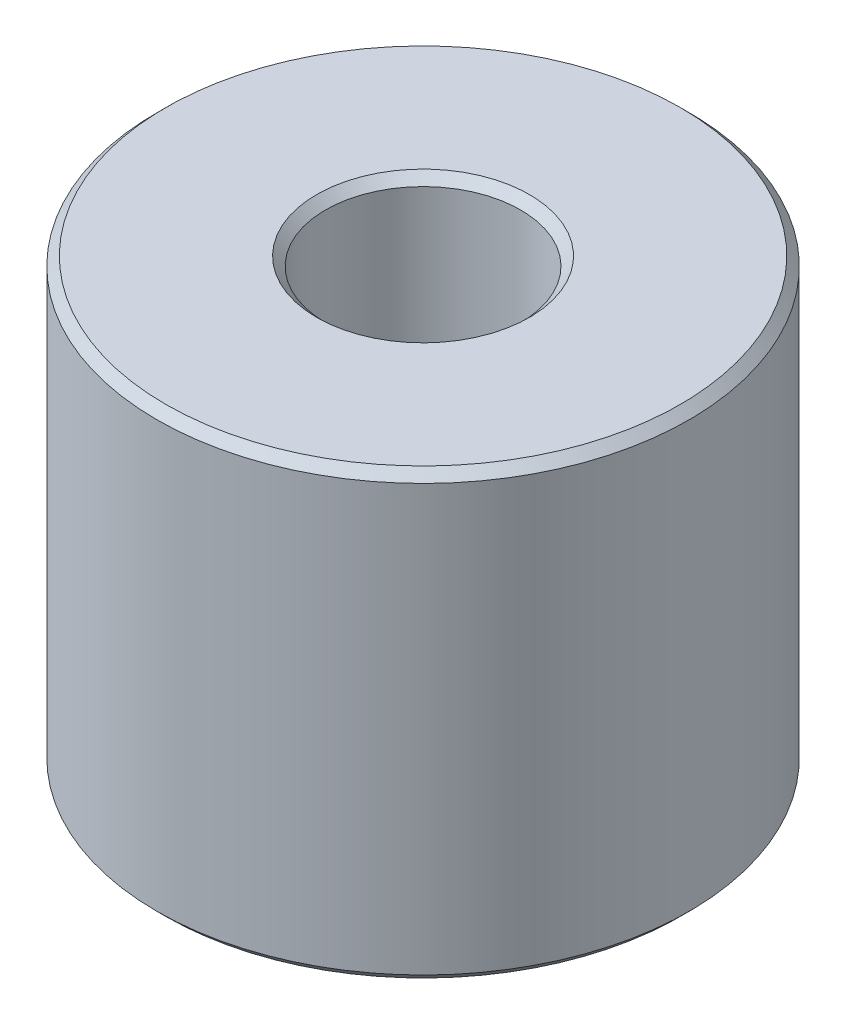
SolidWorks part; units mm, degrees
material "S45C"
ref_plane "正面" through (0, 0, 0) normal (0, 0, 1) x (1, 0, 0)
ref_plane "平面" through (0, 0, 0) normal (0, 1, 0) x (1, 0, 0)
ref_plane "右側面" through (0, 0, 0) normal (1, 0, 0) x (0, 0, -1)
sketch "ｽｹｯﾁ1" plane through (0, 0, 0) normal (0, 1, 0) x (1, 0, 0)
  circle A0 centre (0, 0) radius 1.1
  circle A1 centre (0, 0) radius 3
  dimension "D1" = 2.2
  dimension "D2" = 6
extrude "ﾎﾞｽ - 押し出し1" add sketch "ｽｹｯﾁ1" along normal mid plane 5
chamfer "面取り1" distance 0.1 angle 45 4 edges at (0, -2.5, 3) (0, 2.5, 3) (0, -2.5, 1.1) (0, 2.5, 1.1)
